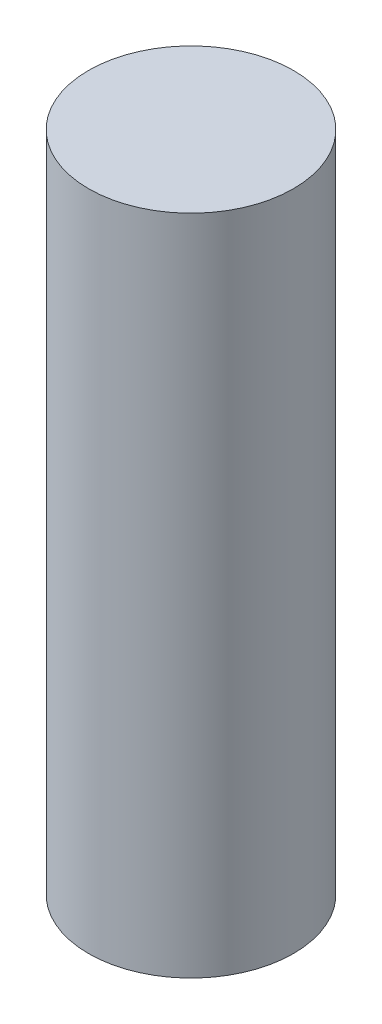
SolidWorks part; units mm, degrees
ref_plane "Plano frontal" through (0, 0, 0) normal (0, 0, 1) x (1, 0, 0)
ref_plane "Plano superior" through (0, 0, 0) normal (0, 1, 0) x (1, 0, 0)
ref_plane "Plano direito" through (0, 0, 0) normal (1, 0, 0) x (0, 0, -1)
sketch "Esboço2" plane through (0, 0, 0) normal (0, 1, 0) x (1, 0, 0)
  circle A0 centre (0, 0) radius 12.375
  dimension "D1" = 24.75
extrude "Ressalto-extrusão1" add sketch "Esboço2" along normal blind 80
shell "Casca2" thickness 2.5
